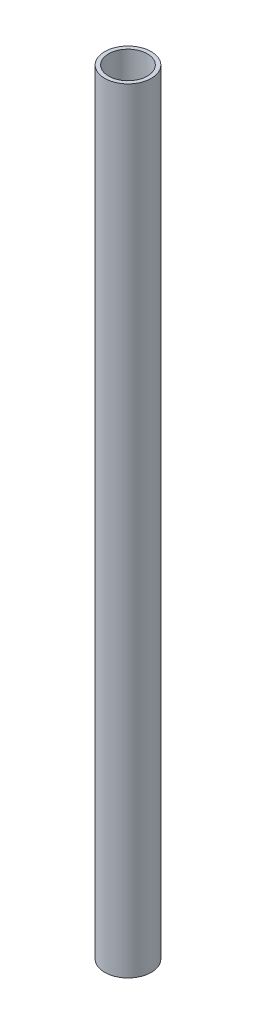
SolidWorks part; units mm, degrees
ref_plane "前视基准面" through (0, 0, 0) normal (0, 0, 1) x (1, 0, 0)
ref_plane "上视基准面" through (0, 0, 0) normal (0, 1, 0) x (1, 0, 0)
ref_plane "右视基准面" through (0, 0, 0) normal (1, 0, 0) x (0, 0, -1)
sketch "Sketch1" plane through (0, 0, 0) normal (0, 1, 0) x (1, 0, 0)
  circle A0 centre (0, 0) radius 5
  circle A1 centre (0, 0) radius 6
extrude "Boss-Extrude1" add sketch "Sketch1" along normal blind 200
